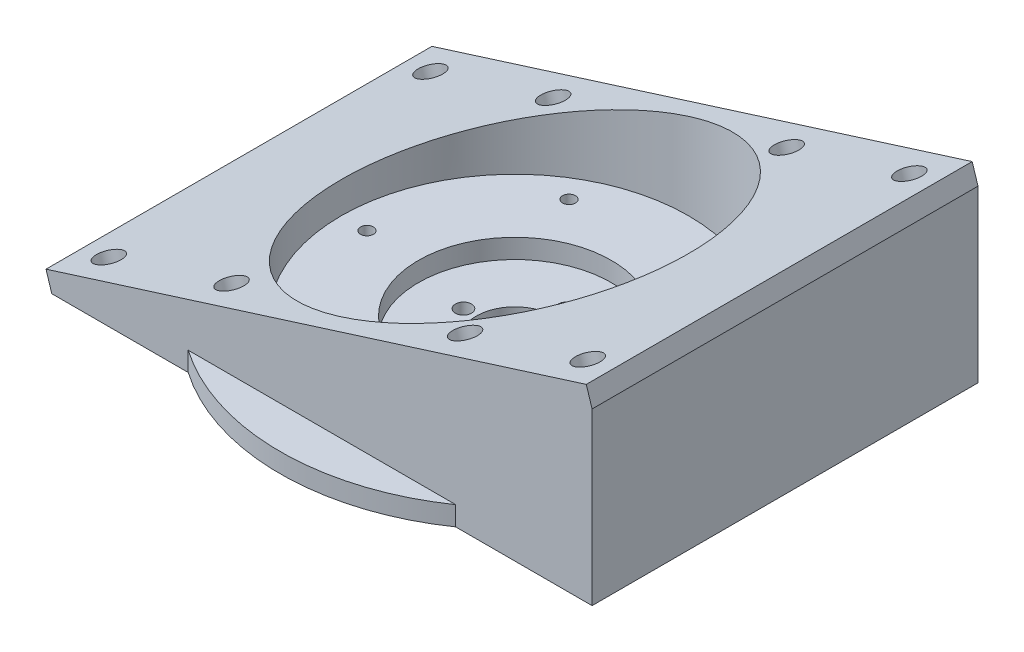
SolidWorks part; units mm, degrees
ref_plane "前视基准面" through (0, 0, 0) normal (0, 0, 1) x (1, 0, 0)
ref_plane "上视基准面" through (0, 0, 0) normal (0, 1, 0) x (1, 0, 0)
ref_plane "右视基准面" through (0, 0, 0) normal (1, 0, 0) x (0, 0, -1)
sketch "草图1" plane through (0, 0, 0) normal (0, 0, 1) x (1, 0, 0)
  line L0 (-67.0824, -7.9577) -> (16.9176, -7.9577)
  line L1 (16.9176, -7.9577) -> (16.9176, 18.5274)
  line L2 (-67.0824, -7.9577) -> (16.9176, 18.5274)
  dimension "D1" = 84
  dimension "D2" = 17.5
extrude "凸台-拉伸1" add sketch "草图1" along normal blind 60
sketch "草图2" plane through (-3.7837, 12.0003, 0) normal (-0.3007, 0.9537, 0) x (0.9537, 0.3007, 0)
  line L1 (-66.3705, 0) -> (21.7059, 0)
  line L2 (-66.3705, 0) -> (-66.3705, -60)
  line L3 (-66.3705, -60) -> (21.7059, -60)
  line L4 (21.7059, 0) -> (21.7059, -60)
extrude "凸台-拉伸2" add sketch "草图2" along normal blind 3
sketch "草图3" plane through (0, -7.9577, 0) normal (0, -1, 0) x (-1, 0, 0)
  line L0 (67.0824, -60) -> (67.0824, 0) construction
  line L2 (67.0824, -60) -> (-16.9176, -60) construction
  circle A0 centre (25.0824, -30) radius 27
  dimension "D1" = 42
  dimension "D2" = 30
extrude "切除-拉伸1" cut sketch "草图3" against normal blind 50
sketch "草图4" plane through (0, -7.9577, 0) normal (0, -1, 0) x (-1, 0, 0)
  circle A0 centre (25.0824, -30) radius 36.5
extrude "凸台-拉伸3" add sketch "草图4" against normal blind 3
sketch "草图13" plane through (0, -4.9577, 0) normal (0, 1, 0) x (1, 0, 0)
  circle A0 centre (-25.0824, -30) radius 20
  circle A1 centre (-25.0824, -30) radius 27 construction
  dimension "D1" = 0
extrude "切除-拉伸3" cut sketch "草图13" against normal blind 60
sketch "草图14" plane through (0, -4.9577, 0) normal (0, 1, 0) x (1, 0, 0)
  circle A0 centre (-48.0824, -30) radius 1
  circle A1 centre (-25.0824, -30) radius 20 construction
  dimension "D1" = 23
  dimension "D2" = 0
extrude "切除-拉伸4" cut sketch "草图14" against normal blind 60
pattern_circular "阵列(圆周)1" count 6 over 360 about axis through (-25.0824, 0, 30) along (0, 1, 0) of "切除-拉伸4"
sketch "草图16" plane through (-4.6858, 14.8615, 0) normal (-0.3007, 0.9537, 0) x (0.9537, 0.3007, 0)
  line L0 (21.7059, 0) -> (-66.3705, 0) construction
  line L1 (-66.3705, 0) -> (-66.3705, -60) construction
  line L2 (-66.3705, -60) -> (21.7059, -60) construction
  circle A0 centre (-61.3705, -5) radius 2
  circle A1 centre (-61.3705, -55) radius 2
  dimension "D1" = 5
  dimension "D3" = 5
  dimension "D2" = 5
  dimension "D4" = 5
extrude "切除-拉伸5" cut sketch "草图16" against normal blind 3
pattern_linear "阵列(线性)1" count 2 spacing 20 along (0.9537, 0.3007, 0) of "切除-拉伸5"
sketch "草图17" plane through (-4.6858, 14.8615, 0) normal (-0.3007, 0.9537, 0) x (0.9537, 0.3007, 0)
  line L0 (21.7059, -60) -> (21.7059, 0) construction
  line L1 (-66.3705, -60) -> (21.7059, -60) construction
  line L2 (21.7059, 0) -> (-66.3705, 0) construction
  circle A0 centre (16.7059, -55) radius 2
  circle A1 centre (16.7059, -5) radius 2
  dimension "D1" = 5
  dimension "D3" = 5
  dimension "D2" = 5
  dimension "D4" = 5
extrude "切除-拉伸6" cut sketch "草图17" against normal blind 3
pattern_linear "阵列(线性)2" count 2 spacing 20 along (-0.9537, -0.3007, 0) of "切除-拉伸6"
sketch "草图18" plane through (0, -4.9577, 0) normal (0, 1, 0) x (1, 0, 0)
  circle A0 centre (-25.0824, -30) radius 20
extrude "凸台-拉伸4" add sketch "草图18" against normal blind 6
sketch "草图19" plane through (0, -4.9577, 0) normal (0, 1, 0) x (1, 0, 0)
  circle A0 centre (-25.0824, -30) radius 6
extrude "切除-拉伸7" cut sketch "草图19" against normal blind 6
sketch "草图20" plane through (0, -4.9577, 0) normal (0, 1, 0) x (1, 0, 0)
  circle A0 centre (-25.0824, -30) radius 15
extrude "切除-拉伸8" cut sketch "草图20" against normal blind 3
sketch "草图21" plane through (0, -7.9577, 0) normal (0, 1, 0) x (1, 0, 0)
  circle A0 centre (-33.0824, -30) radius 1.25
  circle A1 centre (-25.0824, -30) radius 6 construction
  dimension "D1" = 0
  dimension "D2" = 8
extrude "切除-拉伸9" cut sketch "草图21" against normal blind 3
pattern_circular "阵列(圆周)2" count 4 over 360 about axis through (-25.0824, 0, 30) along (0, 1, 0) of "切除-拉伸9"
